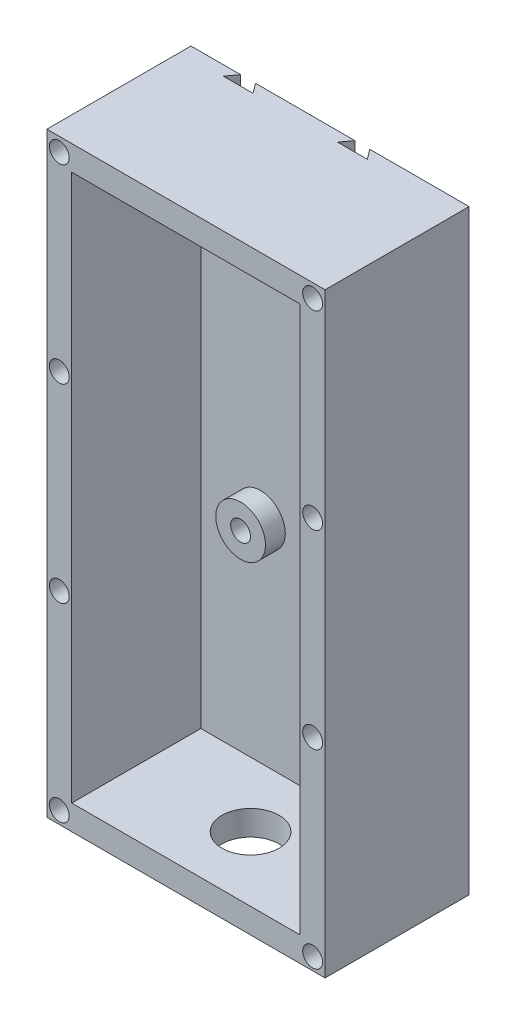
SolidWorks part; units mm, degrees
ref_plane "Přední rovina" through (0, 0, 0) normal (0, 0, 1) x (1, 0, 0)
ref_plane "Horní rovina" through (0, 0, 0) normal (0, 1, 0) x (1, 0, 0)
ref_plane "Pravá rovina" through (0, 0, 0) normal (1, 0, 0) x (0, 0, -1)
sketch "Skica1" plane through (0, 0, 0) normal (0, 0, 1) x (1, 0, 0)
  line L0 (-104, -13) -> (-114, -13) construction
  line L1 (-114, 107) -> (-58, 107)
  line L2 (-114, 107) -> (-114, -13)
  line L3 (-114, -13) -> (-58, -13)
  line L4 (-58, 107) -> (-58, -13)
  dimension "D1" = 56
extrude "Přidat vysunutím1" add sketch "Skica1" along normal blind 3
sketch "Skica2" plane through (0, 0, 3) normal (0, 0, 1) x (1, 0, 0)
  line L0 (-63, -8) -> (-109, -8)
  line L1 (-58, 107) -> (-114, 107)
  line L2 (-58, 107) -> (-58, -13)
  line L3 (-58, -13) -> (-114, -13)
  line L4 (-114, 107) -> (-114, -13)
  line L5 (-109, 102) -> (-109, -8)
  line L6 (-63, 102) -> (-109, 102)
  line L7 (-63, 102) -> (-63, -8)
  dimension "D2" = 46
  dimension "D1" = 5
extrude "Přidat vysunutím2" add sketch "Skica2" along normal blind 26 separate body
sketch "Skica3" plane through (0, -13, 0) normal (0, -1, 0) x (1, 0, 0)
  line L2 (-114, 3) -> (-58, 3) construction
  line L3 (-114, 29) -> (-114, 3) construction
  circle A0 centre (-86, 16) radius 5.75
  point P9 (-86, 3)
  point P10 (-114, 16)
  dimension "D1" = 11.5
extrude "Odebrat vysunutím1" cut sketch "Skica3" against normal up to surface (5 mm away) up to face at (-86, -8, 16)
sketch "Skica4" plane through (0, 0, 3) normal (0, 0, 1) x (1, 0, 0)
  line L0 (-109, 102) -> (-109, -8) construction
  line L1 (-63, 102) -> (-109, 102) construction
  line L2 (-97, 87.5) -> (-97, 34.5) construction
  line L3 (-63, -8) -> (-63, 102) construction
  line L4 (-97, 87.5) -> (-75, 87.5) construction
  line L5 (-109, 20) -> (-63, 20) construction
  line L6 (-86, 87.5) -> (-86, 34.5) construction
  line L7 (-109, -8) -> (-63, -8) construction
  circle A0 centre (-97, 87.5) radius 2
  circle A1 centre (-97, 87.5) radius 5
  circle A2 centre (-97, 34.5) radius 2
  circle A3 centre (-97, 34.5) radius 5
  circle A4 centre (-75, 34.5) radius 5
  circle A5 centre (-75, 34.5) radius 2
  circle A6 centre (-75, 87.5) radius 5
  circle A7 centre (-75, 87.5) radius 2
  dimension "D1" = 4
  dimension "D2" = 10
  dimension "D3" = 12
  dimension "D4" = 14.5
  dimension "D5" = 53
  dimension "D6" = 34
  dimension "D7" = 22
  dimension "D8" = 14.5
  dimension "D9" = 12
  dimension "D10" = 23
  dimension "D11" = 28
extrude "Přidat vysunutím3" add sketch "Skica4" along normal blind 4
sketch "Skica5" plane through (0, 0, 29) normal (0, 0, 1) x (1, 0, 0)
  line L0 (-114, 107) -> (-114, -13) construction
  line L1 (-114, -13) -> (-58, -13) construction
  line L2 (-58, 107) -> (-114, 107) construction
  line L4 (-58, -13) -> (-58, 107) construction
  line L5 (-60.5, 27.75) -> (-58.5, 27.75) construction
  line L6 (-58.5, 27.75) -> (-58.5, -10.5) construction
  circle A0 centre (-111.5, -10.5) radius 2
  circle A1 centre (-60.5, -10.5) radius 2
  circle A2 centre (-60.5, 27.75) radius 2
  circle A3 centre (-60.5, 66) radius 2
  circle A4 centre (-60.5, 104.25) radius 2
  circle A5 centre (-111.5, 27.75) radius 2
  circle A6 centre (-111.5, 66) radius 2
  circle A7 centre (-111.5, 104.25) radius 2
  dimension "D3" = 4
  dimension "D1" = 2.5
  dimension "D2" = 2.5
  dimension "D6" = 38.25
  dimension "D7" = 2.75
  dimension "D8" = 2.5
  dimension "D9" = 2.5
  dimension "D10" = 2.75
  dimension "D11" = 2.5
  dimension "D12" = 2.5
  dimension "D13" = 38.25
  dimension "D14" = 38.25
  dimension "D15" = 0.5
  dimension "D4" = 2
  dimension "D5" = 4
extrude "Odebrat vysunutím2" cut sketch "Skica5" against normal blind 4
sketch "Skica6" plane through (0, 107, 0) normal (0, 1, 0) x (1, 0, 0)
  line L0 (-104, 0) -> (-105.5, -2)
  line L1 (-105.5, -2) -> (-99.5, -2)
  line L2 (-99.5, -2) -> (-101, 0)
  line L3 (-101, 0) -> (-104, 0)
  line L4 (-81, 0) -> (-82.5, -2)
  line L5 (-82.5, -2) -> (-76.5, -2)
  line L6 (-76.5, -2) -> (-78, 0)
  line L7 (-78, 0) -> (-81, 0)
extrude "Odebrat vysunutím3" cut sketch "Skica6" against normal through all both and the other way through all
